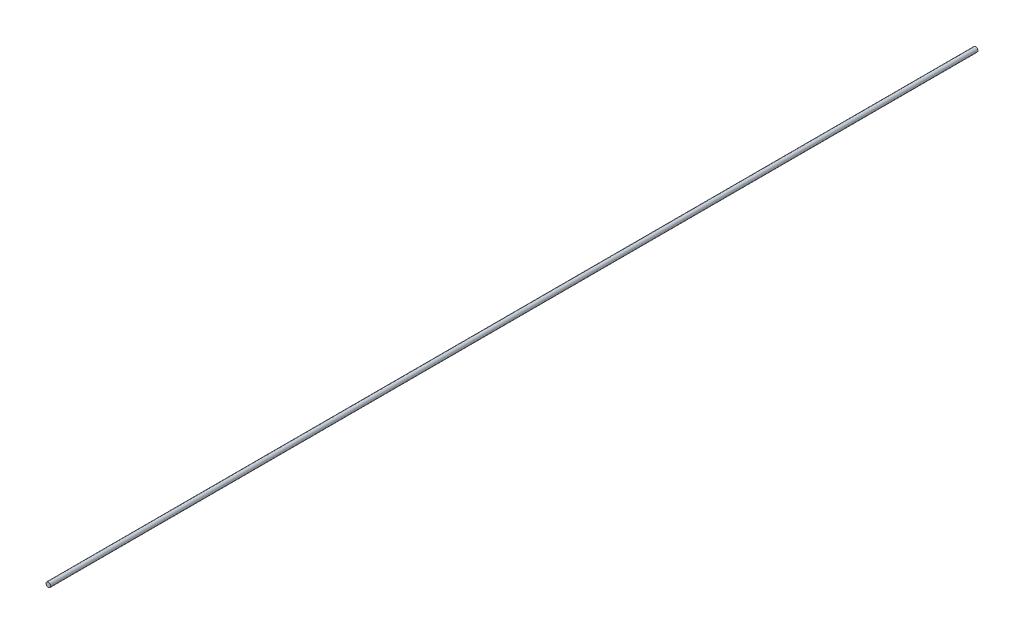
SolidWorks part; units mm, degrees
material "6063-O, Barra estrusa (SS)"
ref_plane "Piano frontale" through (0, 0, 0) normal (0, 0, 1) x (1, 0, 0)
ref_plane "Piano superiore" through (0, 0, 0) normal (0, 1, 0) x (1, 0, 0)
ref_plane "Piano destro" through (0, 0, 0) normal (1, 0, 0) x (0, 0, -1)
sketch "Schizzo1" plane through (0, 0, 0) normal (0, 0, 1) x (1, 0, 0)
  circle A0 centre (0, 0) radius 1.5
  dimension "D1" = 3
extrude "Estrusione-Estrusione1" add sketch "Schizzo1" along normal blind 600
